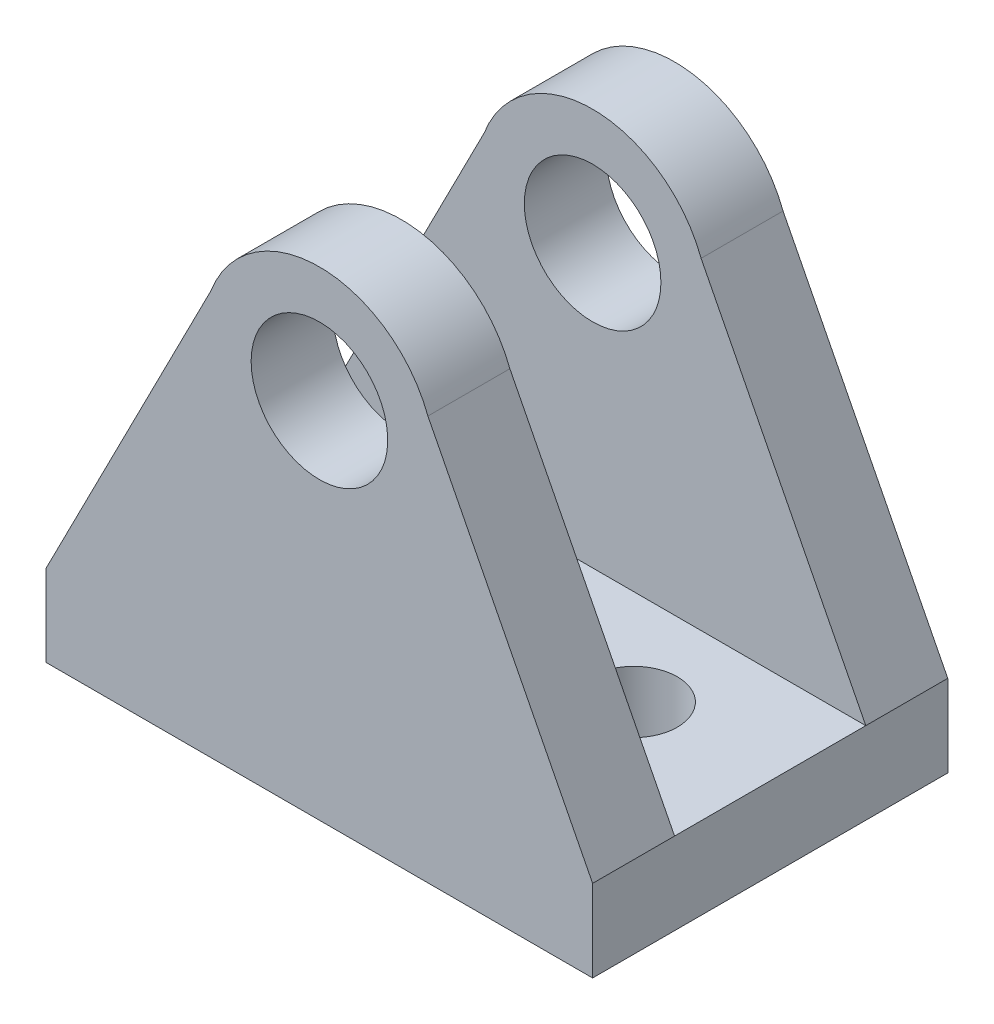
SolidWorks part; units mm, degrees
ref_plane "前视基准面" through (0, 0, 0) normal (0, 0, 1) x (1, 0, 0)
ref_plane "上视基准面" through (0, 0, 0) normal (0, 1, 0) x (1, 0, 0)
ref_plane "右视基准面" through (0, 0, 0) normal (1, 0, 0) x (0, 0, -1)
ref_plane "基准面4" through (0, 3, 0) normal (0, 1, 0) x (1, 0, 0)
sketch "草图1" plane through (0, 3, 0) normal (0, 1, 0) x (1, 0, 0)
  line L0 (45.3431, 51.2194) -> (25.3431, 51.2194)
  line L1 (25.3431, 51.2194) -> (25.3431, 44.2194)
  line L2 (25.3431, 44.2194) -> (45.3431, 44.2194)
  line L3 (45.3431, 44.2194) -> (45.3431, 51.2194)
extrude "凸台-拉伸1" add sketch "草图1" against normal blind 3
sketch "草图2" plane through (0, 0, -44.2194) normal (0, 0, 1) x (1, 0, 0)
  line L0 (45.3431, 0) -> (25.3431, 0)
  line L1 (25.3431, 0) -> (25.3431, 3)
  line L2 (25.3431, 3) -> (31.3722, 14.8)
  line L3 (39.314, 14.8) -> (45.3431, 3)
  line L4 (45.3431, 3) -> (45.3431, 0)
  arc A0 (31.3722, 14.8) -> (39.314, 14.8) centre (35.3431, 13.3) cw
extrude "凸台-拉伸2" add sketch "草图2" along normal blind 3
sketch "草图3" plane through (0, 0, -51.2194) normal (0, 0, -1) x (-1, 0, 0)
  line L0 (-25.3431, 0) -> (-45.3431, 0)
  line L1 (-45.3431, 0) -> (-45.3431, 3)
  line L2 (-45.3431, 3) -> (-39.314, 14.8)
  line L3 (-31.3722, 14.8) -> (-25.3431, 3)
  line L4 (-25.3431, 3) -> (-25.3431, 0)
  arc A0 (-39.314, 14.8) -> (-31.3722, 14.8) centre (-35.3431, 13.3) cw
extrude "凸台-拉伸3" add sketch "草图3" along normal blind 3
hole_wizard "Ø3.2 (3.2) 直径孔1" positions "草图5" profile "草图4" hole size "Ø3.2" standard "ANSI Metric"
sketch "草图5" plane through (0, 0, 0) normal (0, -1, 0) x (-1, 0, 0)
  point P0 (-40.3431, 47.7194)
  point P1 (-30.3431, 47.7194)
sketch "草图4" plane through (40.3431, 0, -47.7194) normal (1, 0, 0) x (0, 0, -1)
  line L0 (0, 0) -> (0, 17.5448)
  line L1 (0, 17.5448) -> (1.6, 17.5448)
  line L2 (1.6, 17.5448) -> (1.6, 0)
  line L5 (1.6, 0) -> (0, 0)
  line L11 (0, -6.35) -> (0, 107.95) construction
  dimension "通孔孔直径" = 3.2
  dimension "通孔孔深度" = 17.5448
hole_wizard "Ø5.0 (5) 直径孔1" positions "草图7" profile "草图6" hole size "Ø5.0" standard "ANSI Metric"
sketch "草图7" plane through (0, 0, -54.2194) normal (0, 0, -1) x (-1, 0, 0)
  point P0 (-35.3431, 13.3)
sketch "草图6" plane through (35.3431, 13.3, -54.2194) normal (1, 0, 0) x (0, 1, 0)
  line L0 (0, 0) -> (0, 3)
  line L1 (0, 3) -> (2.5, 3)
  line L2 (2.5, 3) -> (2.5, 0)
  line L5 (2.5, 0) -> (0, 0)
  line L11 (0, -6.35) -> (0, 107.95) construction
  dimension "通孔孔直径" = 5
  dimension "通孔孔深度" = 3
hole_wizard "Ø5.0 (5) 直径孔2" positions "草图9" profile "草图8" hole size "Ø5.0" standard "ANSI Metric"
sketch "草图9" plane through (0, 0, -44.2194) normal (0, 0, -1) x (-1, 0, 0)
  point P0 (-35.3431, 13.3)
sketch "草图8" plane through (35.3431, 13.3, -44.2194) normal (1, 0, 0) x (0, 1, 0)
  line L0 (0, 0) -> (0, 3)
  line L1 (0, 3) -> (2.5, 3)
  line L2 (2.5, 3) -> (2.5, 0)
  line L5 (2.5, 0) -> (0, 0)
  line L11 (0, -6.35) -> (0, 107.95) construction
  dimension "通孔孔直径" = 5
  dimension "通孔孔深度" = 3
